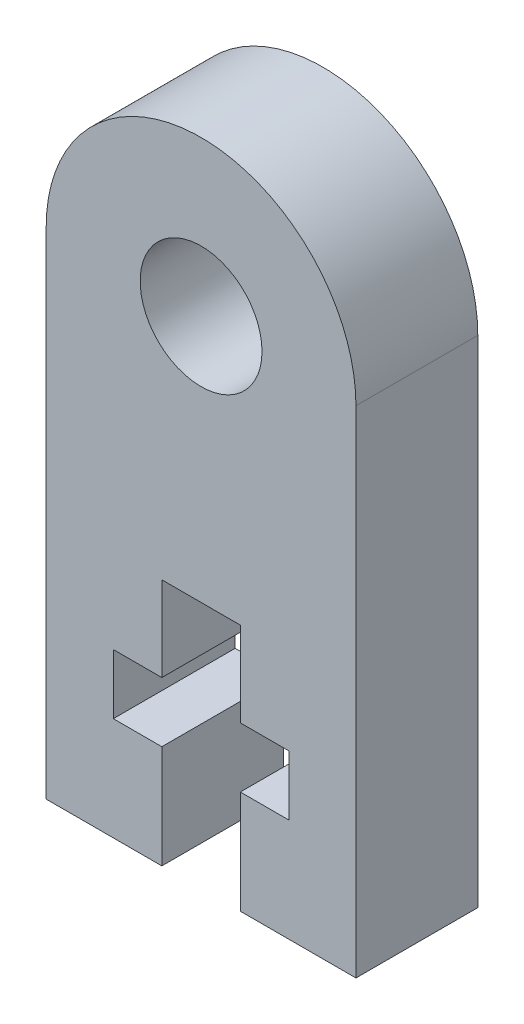
SolidWorks part; units mm, degrees
ref_plane "Front Plane" through (0, 0, 0) normal (0, 0, 1) x (1, 0, 0)
ref_plane "Top Plane" through (0, 0, 0) normal (0, 1, 0) x (1, 0, 0)
ref_plane "Right Plane" through (0, 0, 0) normal (1, 0, 0) x (0, 0, -1)
sketch "Sketch1" plane through (0, 0, 0) normal (0, 0, 1) x (1, 0, 0)
  line L0 (0, 0) -> (-2.086, 2.086) construction
  line L1 (0, 0) -> (0, 2.95) construction
  line L2 (-7.5, 0) -> (-7.5, -24)
  line L3 (-7.5, -24) -> (7.5, -24)
  line L4 (7.5, -24) -> (7.5, 0)
  line L5 (0, 0) -> (0, -24) construction
  circle A0 centre (0, 0) radius 2.95
  arc A1 (-7.5, 0) -> (7.5, 0) centre (0, 0) cw
  dimension "D1" = 5.9
  dimension "D4" = 45
  dimension "D5" = 24
  dimension "D6" = 15
extrude "Boss-Extrude1" add sketch "Sketch1" along normal blind 5.9
sketch "Sketch3" plane through (0, 0, 5.9) normal (0, 0, 1) x (1, 0, 0)
  line L0 (-7.5, -24) -> (7.5, -24) construction
  line L1 (-1.9, -24) -> (1.9, -24)
  line L2 (-1.9, -24) -> (-1.9, -19)
  line L3 (-1.9, -12) -> (1.9, -12)
  line L4 (1.9, -24) -> (1.9, -19)
  line L5 (0, -12) -> (0, 0) construction
  line L6 (1.9, -16.1) -> (4.25, -16.1)
  line L7 (-4.25, -16.1) -> (-1.9, -16.1)
  line L8 (-4.25, -16.1) -> (-4.25, -19)
  line L9 (-4.25, -19) -> (-1.9, -19)
  line L10 (4.25, -16.1) -> (4.25, -19)
  line L11 (-1.9, -16.1) -> (-1.9, -12)
  line L12 (1.9, -19) -> (4.25, -19)
  line L13 (1.9, -16.1) -> (1.9, -12)
  point P18 (-3.075, -19)
  dimension "D1" = 3.8
  dimension "D3" = 12
  dimension "D4" = 8.5
  dimension "D5" = 2.9
  dimension "D6" = 5
extrude "Cut-Extrude2" cut sketch "Sketch3" against normal through all
equation "\"smallPulleyTeeth\"= 15"
equation "\"largePulleyTeeth\"= 40"
equation "\"eighthThick\"= 2.9mm"
equation "\"sixteenthThick\" = 1.7mm"
equation "\"quarterThick\"=5.9mm"
equation "\"OD\" = 145mm"
equation "\"puckAngle\" = 60.5deg"
equation "\"puckDiam\" = 76.5mm"
equation "\"axlePress\" = 5.9mm"
equation "\"D1@Sketch1\"=\"axlePress\""
equation "\"D1@Boss-Extrude1\"=\"quarterThick\""
equation "\"press\" = 0.2mm"
equation "\"wheelClear\" = 0.3mm"
equation "\"10-32clear\" = 4.5mm"
equation "\"D1@Sketch3\"=\"8-32clear\"-\"press\""
equation "\"6-32clear\" = 3.3mm"
equation "\"8-32clear\" = 4.0mm"
equation "\"wheelHeight\" = 24mm"
equation "\"D5@Sketch1\"=\"wheelHeight\""
